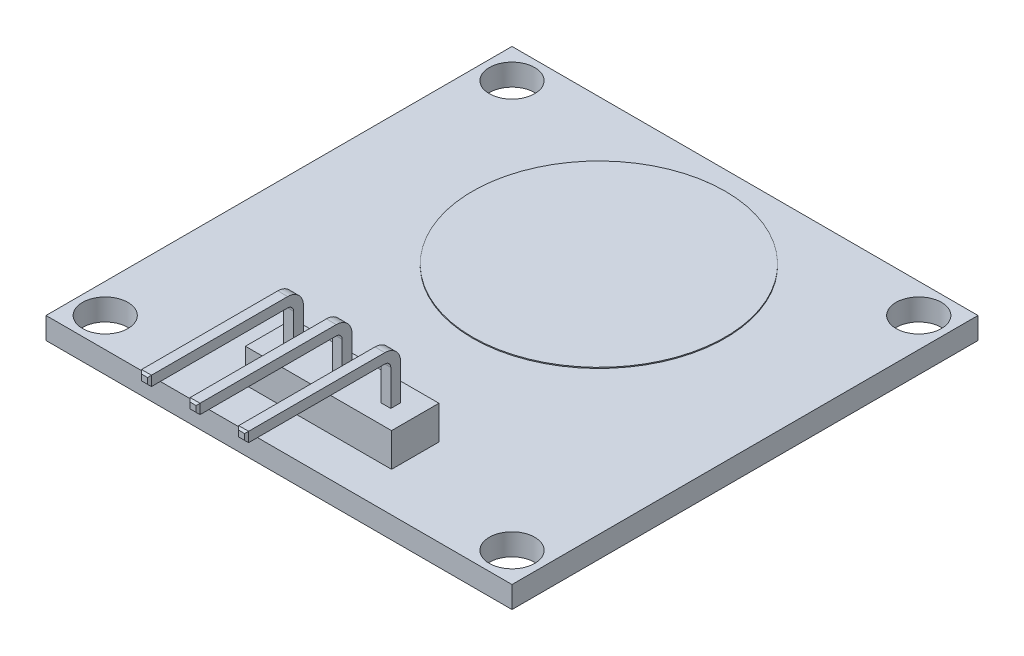
SolidWorks part; units mm, degrees
ref_plane "前视基准面" through (0, 0, 0) normal (0, 0, 1) x (1, 0, 0)
ref_plane "上视基准面" through (0, 0, 0) normal (0, 1, 0) x (1, 0, 0)
ref_plane "右视基准面" through (0, 0, 0) normal (1, 0, 0) x (0, 0, -1)
sketch "草图1" plane through (0, 0, 0) normal (0, 1, 0) x (1, 0, 0)
  line L1 (-11.8, 11.8) -> (11.8, 11.8)
  line L2 (-11.8, 11.8) -> (-11.8, -11.8)
  line L3 (-11.8, -11.8) -> (11.8, -11.8)
  line L4 (11.8, 11.8) -> (11.8, -11.8)
  line L5 (-11.8, 11.8) -> (11.8, -11.8) construction
  line L6 (-11.8, -11.8) -> (11.8, 11.8) construction
  point P0 (0, 0)
  dimension "D1" = 23.6
  dimension "D2" = 23.6
extrude "凸台-拉伸1" add sketch "草图1" along normal blind 1.1
sketch "草图2" plane through (0, 1.1, 0) normal (0, 1, 0) x (1, 0, 0)
  line L0 (11.8, -11.8) -> (11.8, 11.8) construction
  line L1 (-11.8, -11.8) -> (11.8, -11.8) construction
  circle A0 centre (10.3, -10.3) radius 1.15
  dimension "D1" = 2.3
  dimension "D2" = 1.5
  dimension "D3" = 1.5
extrude "切除-拉伸1" cut sketch "草图2" against normal up to next
mirror "镜向1" about plane through (0, 0, 0) normal (1, 0, 0) of "切除-拉伸1"
mirror "镜向2" about plane through (0, 0, 0) normal (0, 0, 1) of "镜向1", "切除-拉伸1"
sketch "草图3" plane through (0, 1.1, 0) normal (0, 1, 0) x (1, 0, 0)
  line L0 (-11.8, -11.8) -> (11.8, -11.8) construction
  line L1 (-3.7, -7.4) -> (3.7, -7.4)
  line L2 (-3.7, -7.4) -> (-3.7, -9.8)
  line L3 (-3.7, -9.8) -> (3.7, -9.8)
  line L4 (3.7, -7.4) -> (3.7, -9.8)
  line L5 (-3.7, -7.4) -> (3.7, -9.8) construction
  line L6 (-3.7, -9.8) -> (3.7, -7.4) construction
  point P0 (0, -8.6)
  dimension "D1" = 7.4
  dimension "D2" = 2.4
  dimension "D3" = 2
extrude "凸台-拉伸2" add sketch "草图3" along normal blind 1.7
sketch "草图4" plane through (0, 0, 0) normal (1, 0, 0) x (0, 0, -1)
  line L0 (-8.35, -1.6) -> (-8.35, 5.4)
  line L1 (-8.35, 5.4) -> (-16.15, 5.4)
  line L2 (-16.15, 5.4) -> (-16.15, 4.9)
  line L3 (-16.15, 4.9) -> (-8.85, 4.9)
  line L4 (-8.85, 4.9) -> (-8.85, -1.6)
  line L5 (-8.85, -1.6) -> (-8.35, -1.6)
  line L6 (-9.8, 2.8) -> (-7.4, 2.8) construction
  line L7 (-11.8, 1.1) -> (11.8, 1.1) construction
  point P2 (-8.6, 2.8)
  point P9 (-8.6, -1.6)
  dimension "D1" = 0.5
  dimension "D2" = 0.5
  dimension "D3" = 4.3
  dimension "D4" = 7
  dimension "D5" = 7.8
extrude "凸台-拉伸3" add sketch "草图4" along normal mid plane 0.5
chamfer "倒角7" distance 0.1 angle 45 8 edges at (0, -1.6, 8.85) (0.25, -1.6, 8.6) (0, -1.6, 8.35) (-0.25, -1.6, 8.6) (0, 4.9, 16.15) (0.25, 5.15, 16.15) (-0.25, 5.15, 16.15) (0, 5.4, 16.15)
fillet "圆角1" radius 0.3 1 edges at (0, 4.9, 8.85)
fillet "圆角2" radius 0.8 1 edges at (0, 5.4, 8.35)
pattern_linear "阵列(线性)2" count 2 spacing 2.46 along (1, 0, 0) of "圆角2", "圆角1", "倒角7", "凸台-拉伸3"
pattern_linear "阵列(线性)3" count 2 spacing 2.46 along (-1, 0, 0) of "圆角2", "圆角1", "倒角7", "凸台-拉伸3"
sketch "草图5" plane through (0, 1.1, 0) normal (0, 1, 0) x (1, 0, 0)
  line L0 (11.8, 11.8) -> (-11.8, 11.8) construction
  circle A0 centre (0, 4.4) radius 6.4
  dimension "触摸面板" = 12.8
  dimension "D2" = 7.4
sketch "草图7" plane through (0, 0, 0) normal (0, 1, 0) x (1, 0, 0)
  circle A0 centre (0, 4.4) radius 6.4 construction
  circle A1 centre (0, 4.4) radius 6.4
extrude "凸台-拉伸10" add sketch "草图7" along normal mid plane 1.2 from offset 0.55
sketch "草图8" plane through (0, 0, 0) normal (0, -1, 0) x (1, 0, 0)
  line L1 (-4.5042, 9.6774) -> (4.0972, 9.6774)
  line L2 (-4.5042, 9.6774) -> (-4.5042, 7.561)
  line L3 (-4.5042, 7.561) -> (4.0972, 7.561)
  line L4 (4.0972, 9.6774) -> (4.0972, 7.561)
extrude "背面插座端口切除" cut sketch "草图8" along normal up to surface (1.6 mm away) up to face at (-2.46, -1.6, 8.6)
equation "\"0.2.00mm\"=10"
equation "\"D2@草图5\"=\"触摸面板\"/2+1mm"
